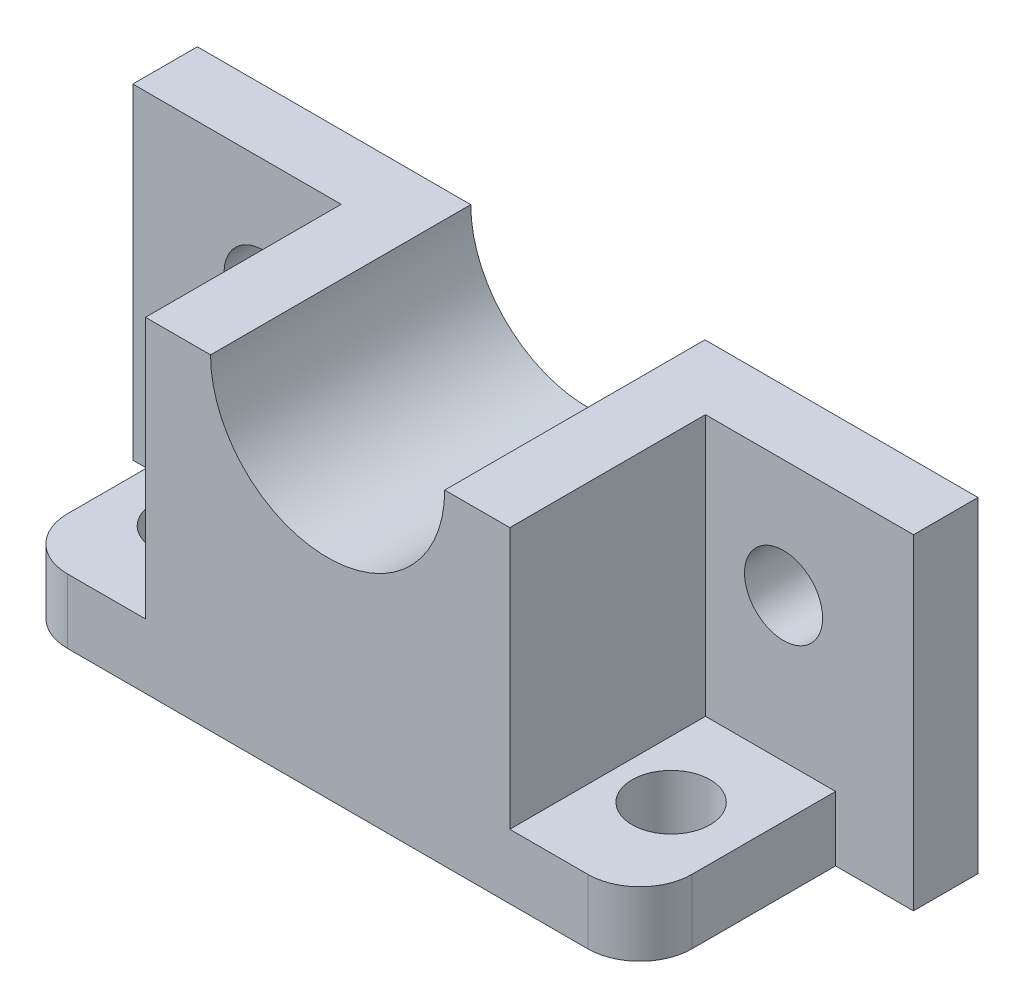
SolidWorks part; units mm, degrees
ref_plane "Front Plane" through (0, 0, 0) normal (0, 0, 1) x (1, 0, 0)
ref_plane "Top Plane" through (0, 0, 0) normal (0, 1, 0) x (1, 0, 0)
ref_plane "Right Plane" through (0, 0, 0) normal (1, 0, 0) x (0, 0, -1)
sketch "Sketch1" plane through (0, 0, 0) normal (0, 0, 1) x (1, 0, 0)
  line L0 (-28.575, 0) -> (-95.2928, 0)
  line L1 (-95.2928, 0) -> (-95.2928, -79.502)
  line L2 (-95.2928, -79.502) -> (95.2072, -79.502)
  line L3 (95.2072, -79.502) -> (95.2072, 0)
  line L4 (95.2072, 0) -> (28.575, 0)
  line L5 (0, 0) -> (0, -45.3247) construction
  arc A2 (-28.575, 0) -> (28.575, 0) centre (0, 0) ccw
  dimension "D1" = 57.15
  dimension "D2" = 79.502
  dimension "D3" = 190.5
extrude "Boss-Extrude1" add sketch "Sketch1" along normal blind 15.748 contours L1 L2 L3 L4 A2 L0
sketch "Sketch2" plane through (0, 0, 15.748) normal (0, 0, 1) x (1, 0, 0)
  line L0 (-44.45, 0) -> (-44.45, -79.502)
  line L1 (-28.575, 0) -> (-95.2928, 0) construction
  line L2 (-95.2928, -79.502) -> (95.2072, -79.502) construction
  line L3 (44.45, 0) -> (44.45, -79.502)
  line L4 (95.2072, 0) -> (28.575, 0) construction
  line L5 (0, 0) -> (0, -79.502) construction
  line L11 (-28.575, 0) -> (-95.2928, 0)
  line L12 (-95.2928, 0) -> (-95.2928, -79.502)
  line L13 (-95.2928, -79.502) -> (95.2072, -79.502)
  line L14 (95.2072, -79.502) -> (95.2072, 0)
  line L15 (95.2072, 0) -> (28.575, 0)
  line L16 (-28.575, 0) -> (-44.45, 0)
  line L18 (-44.45, -79.502) -> (44.45, -79.502)
  line L20 (44.45, 0) -> (28.575, 0)
  arc A1 (-28.575, 0) -> (28.575, 0) centre (0, 0) ccw
  arc A2 (-28.575, 0) -> (28.575, 0) centre (0, 0) ccw
  dimension "D1" = 88.9
  dimension "D2" = 0
extrude "Boss-Extrude3" add sketch "Sketch2" along normal blind 47.752
sketch "Sketch4" plane through (0, -79.502, 0) normal (0, -1, 0) x (1, 0, 0)
  line L0 (-44.45, 63.5) -> (44.45, 63.5) construction
  line L1 (-44.45, 15.748) -> (-76.2, 15.748)
  line L2 (-44.45, 15.748) -> (-44.45, 63.5)
  line L3 (-44.45, 63.5) -> (-76.2, 63.5)
  line L4 (-76.2, 15.748) -> (-76.2, 63.5)
  line L5 (44.45, 15.748) -> (76.2, 15.748)
  line L6 (44.45, 15.748) -> (44.45, 63.5)
  line L7 (44.45, 63.5) -> (76.2, 63.5)
  line L8 (76.2, 15.748) -> (76.2, 63.5)
  line L9 (0, 0) -> (0, 63.5) construction
  dimension "D1" = 152.4
extrude "Boss-Extrude4" add sketch "Sketch4" against normal blind 15.748
fillet "Fillet1" radius 12.7 2 edges at (76.2, -71.628, 63.5) (-76.2, -71.628, 63.5)
sketch "Sketch5" plane through (0, 0, 15.748) normal (0, 0, 1) x (1, 0, 0)
  line L0 (0, 0) -> (0, -79.502) construction
  line L1 (-63.5, -79.502) -> (63.5, -79.502) construction
  circle A0 centre (63.5, -28.702) radius 9.525
  circle A1 centre (-63.5, -28.702) radius 9.525
  point P9 (0, 0)
  dimension "D3" = 19.05
  dimension "D1" = 127
  dimension "D2" = 50.8
extrude "Cut-Extrude1" cut sketch "Sketch5" against normal through all both and the other way through all
sketch "Sketch6" plane through (0, -63.754, 0) normal (0, 1, 0) x (1, 0, 0)
  line L0 (0, 0) -> (0, -63.5) construction
  line L1 (-28.575, -63.5) -> (28.575, -63.5) construction
  line L2 (63.5, -63.5) -> (44.45, -63.5) construction
  circle A0 centre (-58.42, -38.1) radius 9.525
  circle A1 centre (58.42, -38.1) radius 9.525
  point P4 (0, 0)
  dimension "D1" = 19.05
  dimension "D2" = 116.84
  dimension "D3" = 25.4
extrude "Cut-Extrude2" cut sketch "Sketch6" against normal through all both
